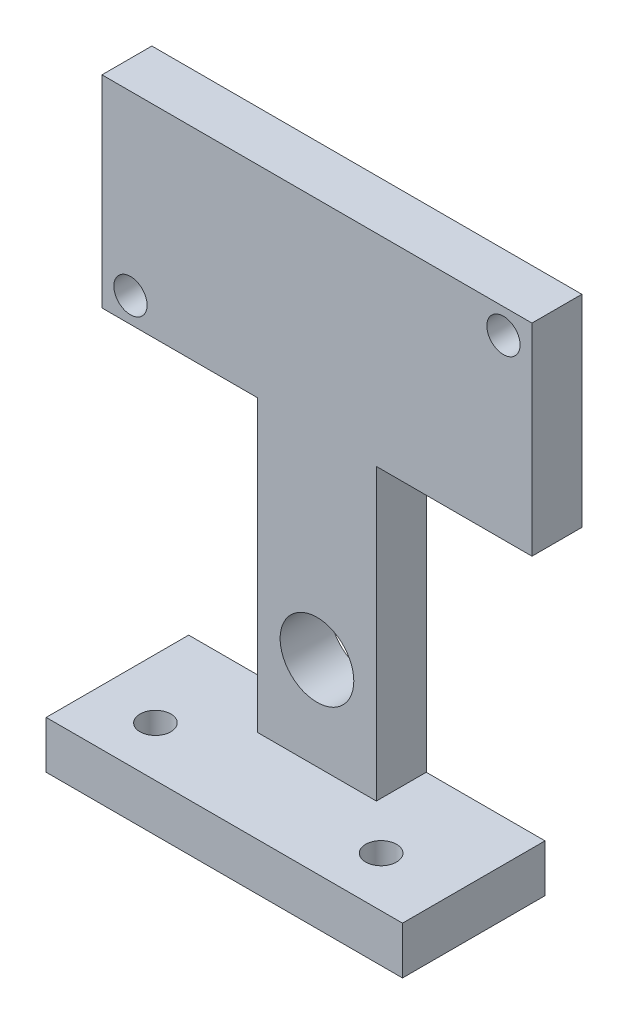
SolidWorks part; units mm, degrees
ref_plane "Front Plane" through (0, 0, 0) normal (0, 0, 1) x (1, 0, 0)
ref_plane "Top Plane" through (0, 0, 0) normal (0, 1, 0) x (1, 0, 0)
ref_plane "Right Plane" through (0, 0, 0) normal (1, 0, 0) x (0, 0, -1)
sketch "Sketch1" plane through (0, 0, 0) normal (0, 1, 0) x (1, 0, 0)
  line L1 (-100.9616, 61.8132) -> (-62.8616, 61.8132)
  line L2 (-100.9616, 61.8132) -> (-100.9616, 46.5732)
  line L3 (-100.9616, 46.5732) -> (-62.8616, 46.5732)
  line L4 (-62.8616, 61.8132) -> (-62.8616, 46.5732)
  dimension "D1" = 38.1
  dimension "D2" = 15.24
extrude "Boss-Extrude1" add sketch "Sketch1" against normal blind 5.08
sketch "Sketch2" plane through (0, 0, 0) normal (0, 1, 0) x (1, 0, 0)
  line L0 (-62.8616, 61.8132) -> (-100.9616, 61.8132) construction
  line L1 (-94.6116, 51.9072) -> (-102.2316, 51.9072) construction
  line L2 (-62.8616, 46.5732) -> (-62.8616, 61.8132) construction
  line L6 (-70.4816, 51.9072) -> (-62.8616, 51.9072) construction
  circle A0 centre (-94.6116, 51.9072) radius 1.651
  circle A1 centre (-70.4816, 51.9072) radius 1.651
  dimension "D1" = 3.302
  dimension "D2" = 24.13
  dimension "D3" = 9.906
extrude "Cut-Extrude1" cut sketch "Sketch2" against normal through all
sketch "Sketch3" plane through (0, 0, 0) normal (0, 1, 0) x (1, 0, 0)
  line L0 (-62.8616, 61.8132) -> (-100.9616, 61.8132) construction
  line L1 (-88.2616, 61.8132) -> (-75.5616, 61.8132)
  line L2 (-88.2616, 61.8132) -> (-88.2616, 56.4792)
  line L3 (-88.2616, 56.4792) -> (-75.5616, 56.4792)
  line L4 (-75.5616, 61.8132) -> (-75.5616, 56.4792)
  line L5 (-88.2616, 61.8132) -> (-100.9616, 61.8132) construction
  line L6 (-75.5616, 61.8132) -> (-62.8616, 61.8132) construction
  dimension "D1" = 5.334
  dimension "D2" = 12.7
extrude "Boss-Extrude2" add sketch "Sketch3" along normal blind 30.988
sketch "Sketch6" plane through (0, 30.988, 0) normal (0, 1, 0) x (1, 0, 0)
  line L0 (-75.5616, 56.4792) -> (-75.5616, 61.8132) construction
  line L1 (-104.8986, 61.8132) -> (-58.9246, 61.8132)
  line L2 (-104.8986, 61.8132) -> (-104.8986, 56.4792)
  line L3 (-104.8986, 56.4792) -> (-58.9246, 56.4792)
  line L4 (-58.9246, 61.8132) -> (-58.9246, 56.4792)
  line L5 (-104.8986, 61.8132) -> (-88.2616, 61.8132) construction
  line L6 (-75.5616, 61.8132) -> (-58.9246, 61.8132) construction
  dimension "D1" = 45.974
extrude "Boss-Extrude3" add sketch "Sketch6" along normal blind 21.59
sketch "Sketch7" plane through (0, 0, -56.4792) normal (0, 0, 1) x (1, 0, 0)
  line L0 (-61.9726, 49.911) -> (-58.9246, 49.911) construction
  line L1 (-58.9246, 52.578) -> (-58.9246, 30.988) construction
  line L2 (-101.8506, 33.655) -> (-104.8986, 33.655) construction
  line L3 (-104.8986, 52.578) -> (-104.8986, 30.988) construction
  line L4 (-101.8506, 33.655) -> (-101.8506, 30.988) construction
  line L5 (-104.8986, 30.988) -> (-88.2616, 30.988) construction
  line L6 (-61.9726, 49.911) -> (-61.9726, 52.578) construction
  line L7 (-104.8986, 52.578) -> (-58.9246, 52.578) construction
  circle A0 centre (-101.8506, 33.655) radius 1.778
  circle A1 centre (-61.9726, 49.911) radius 1.778
  dimension "D1" = 3.556
  dimension "D2" = 39.878
  dimension "D3" = 16.256
extrude "Cut-Extrude4" cut sketch "Sketch7" against normal through all
sketch "Sketch8" plane through (0, 0, -56.4792) normal (0, 0, 1) x (1, 0, 0)
  line L0 (-88.2616, 9.906) -> (-81.9116, 9.906) construction
  line L1 (-88.2616, 30.988) -> (-88.2616, 0) construction
  line L2 (-81.9116, 9.906) -> (-75.5616, 9.906) construction
  line L3 (-75.5616, 30.988) -> (-75.5616, 0) construction
  line L4 (-75.5616, 30.988) -> (-58.9246, 30.988) construction
  circle A0 centre (-81.9116, 9.906) radius 3.937
  dimension "D2" = 7.874
  dimension "D1" = 21.082
extrude "Cut-Extrude5" cut sketch "Sketch8" against normal through all
